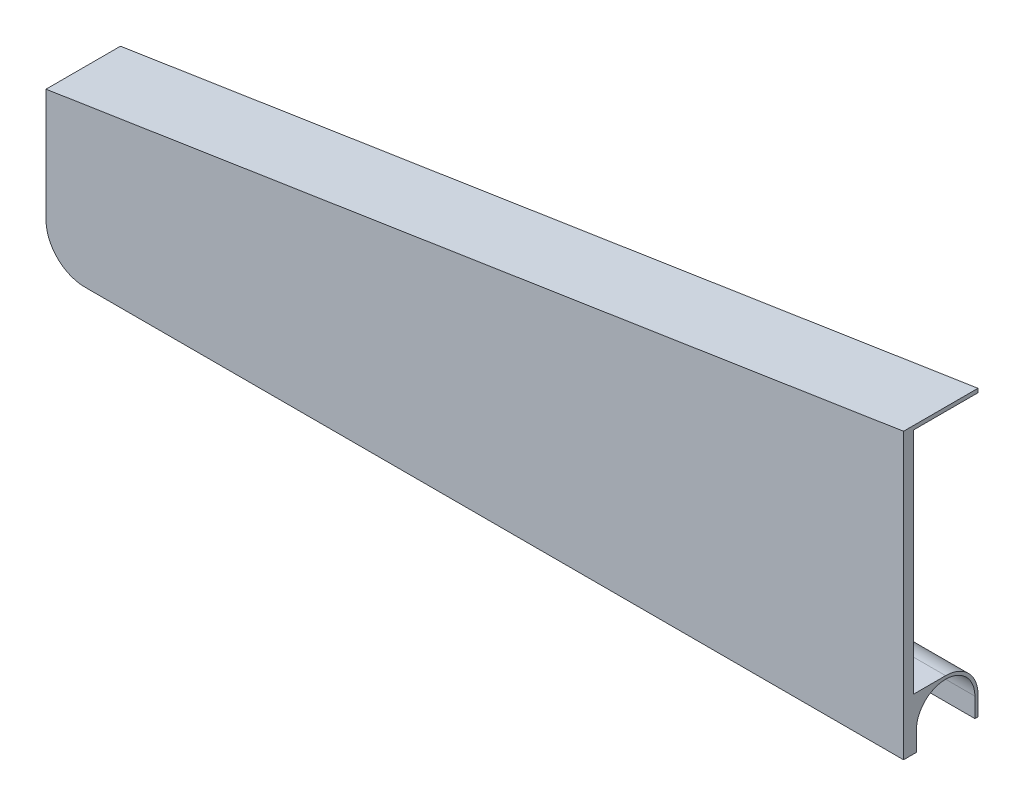
SolidWorks part; units mm, degrees
ref_plane "Front Plane" through (0, 0, 0) normal (0, 0, 1) x (1, 0, 0)
ref_plane "Top Plane" through (0, 0, 0) normal (0, 1, 0) x (1, 0, 0)
ref_plane "Right Plane" through (0, 0, 0) normal (1, 0, 0) x (0, 0, -1)
sketch "Sketch1" plane through (0, 0, 0) normal (0, 0, 1) x (1, 0, 0)
  line L14 (-508.0851, -168.7379) -> (-508.0851, -181.4379)
  line L15 (-482.6851, -206.8379) -> (50.7149, -206.8379)
  line L16 (50.7149, -21.4179) -> (50.7149, -206.8379)
  line L21 (-508.0851, -174.5299) -> (-506.3537, -154.7404) construction
  line L22 (50.7149, -21.4179) -> (-482.6851, -21.4179)
  line L23 (-508.0851, -46.8179) -> (-508.0851, -168.7379)
  line L25 (-280.355, -194.4538) -> (-508.0851, -174.5299) construction
  line L26 (-508.0851, -174.5299) -> (-506.3537, -154.7404) construction
  line L34 (50.264, -26.7703) -> (43.7726, -31.9989) construction
  line L35 (45.1252, -33.9002) -> (50.264, -26.7703) construction
  line L36 (43.7726, -31.9989) -> (45.1252, -33.9002) construction
  line L37 (50.264, -26.7703) -> (-103.8537, -138.7434) construction
  line L44 (-76.0701, -152.5352) -> (-303.6985, -173.5894) construction
  line L45 (-280.355, -194.4538) -> (-508.1812, -175.6608) construction
  arc A13 (-482.6851, -206.8379) -> (-508.0851, -181.4379) centre (-482.6851, -181.4379) cw
  arc A18 (-508.0851, -46.8179) -> (-482.6851, -21.4179) centre (-482.6851, -46.8179) cw
  spline S1 degree 3 poles (-77.3503, -153.028) (-75.7424, -152.4397) (-77.4131, -152.8082) (-78.8159, -153.009) (-82.1955, -153.6301) (-86.3746, -154.3457) (-91.8576, -155.2741) (-98.3546, -156.3306) (-105.8728, -157.5071) (-114.2967, -158.7552) (-123.5384, -160.0448) (-133.4905, -161.3332) (-144.0415, -162.5906) (-155.0756, -163.7834) (-166.472, -164.8921) (-178.1069, -165.8977) (-189.8537, -166.8034) (-201.5813, -167.5892) (-213.0987, -168.327) (-224.299, -168.8253) (-235.081, -169.0417) (-245.4007, -169.0644) (-255.1651, -168.9439) (-264.2735, -168.7565) (-272.6372, -168.5761) (-280.1622, -168.4631) (-286.7666, -168.4772) (-292.3689, -168.6848) (-296.9112, -169.1015) (-300.3402, -169.8135) (-302.7331, -170.728) (-304.0811, -172.4032) (-303.4934, -174.4785) (-301.6135, -176.2656) (-298.6237, -178.2272) (-294.381, -180.2447) (-288.9378, -182.3045) (-282.3217, -184.2798) (-274.6112, -186.0927) (-265.8938, -187.6285) (-256.2798, -188.797) (-245.8908, -189.5049) (-234.8632, -189.681) (-223.3425, -189.2828) (-211.5445, -188.2451) (-199.6188, -186.6868) (-187.6737, -184.833) (-175.7853, -182.6581) (-164.0807, -180.2199) (-152.6882, -177.5689) (-141.7311, -174.7614) (-131.3245, -171.8616) (-121.5743, -168.9396) (-112.5839, -166.062) (-104.4383, -163.3091) (-97.2161, -160.7402) (-91.0087, -158.4393) (-85.7953, -156.4423) (-81.8439, -154.8708) (-78.6405, -153.6118) (-77.3503, -153.028) (-75.7424, -152.4397) (-77.4131, -152.8082) knots -0.012273 -0.005484 -0.001375 0 0.001366 0.005489 0.012269 0.02165 0.033497 0.04769 0.06403 0.082338 0.102396 0.123959 0.146791 0.170641 0.19524 0.220332 0.245646 0.27091 0.295825 0.31977 0.342911 0.365083 0.386049 0.405629 0.423597 0.43978 0.453966 0.466008 0.475784 0.483219 0.48846 0.492078 0.495706 0.500976 0.508553 0.518608 0.53108 0.545907 0.56292 0.581928 0.60273 0.625094 0.648778 0.673537 0.699099 0.724814 0.750772 0.776731 0.802428 0.827555 0.851851 0.875071 0.896936 0.917223 0.935694 0.952169 0.966419 0.978318 0.987727 0.994516 0.998625 1 1.001366 1.005489 1.012269 only from (-76.0701, -152.5352) to (-76.0701, -152.5352) construction
  spline S6 degree 3 poles (43.7726, -31.9989) (42.2447, -33.2296) (40.7155, -34.4587) (37.6488, -36.9065) (36.1121, -38.1263) (31.4913, -41.7719) (28.3962, -44.1844) (19.0706, -51.36) (12.7967, -56.0605) (0.133, -65.2917) (-6.2572, -69.8216) (-19.1386, -78.7336) (-25.6299, -83.1155) (-35.4128, -89.621) (-38.6829, -91.7761) (-43.5886, -95.0079) (-45.2245, -96.0841) (-48.5114, -98.2146) (-50.1629, -99.2681) (-55.1382, -102.3978) (-58.4829, -104.4436) (-65.2122, -108.4767) (-68.5969, -110.4637) (-75.3814, -114.4158) (-78.7813, -116.3795) (-83.8592, -119.3606) (-85.548, -120.3605) (-88.9072, -122.3901) (-90.578, -123.4191) (-93.882, -125.538) (-95.5163, -126.6262) (-97.9049, -128.3604) (-98.6923, -128.9566) (-100.2178, -130.1983) (-100.9587, -130.8423) (-102.0031, -131.8787) (-102.3404, -132.2355) (-102.9811, -132.985) (-103.2858, -133.3815) (-103.8282, -134.2115) (-104.0657, -134.645) (-104.3302, -135.3457) (-104.4023, -135.5859) (-104.5056, -136.0708) (-104.5373, -136.3169) (-104.5503, -136.8183) (-104.5308, -137.0675) (-104.4365, -137.5532) (-104.3615, -137.7939) (-104.1647, -138.253) (-104.0443, -138.4697) (-103.7612, -138.8787) (-103.5969, -139.0714) (-103.2433, -139.4202) (-103.0526, -139.5787) (-102.6488, -139.8696) (-102.4352, -140.0024) (-101.7808, -140.3594) (-101.3217, -140.5456) (-100.3752, -140.8545) (-99.8916, -140.9757) (-98.9196, -141.1683) (-98.4293, -141.2409) (-97.4428, -141.3525) (-96.946, -141.3908) (-95.9572, -141.44) (-95.4638, -141.4515) (-93.986, -141.4541) (-93.0042, -141.4132) (-91.0449, -141.2727) (-90.0677, -141.172) (-88.1168, -140.9234) (-87.1432, -140.7753) (-85.1992, -140.4383) (-84.2286, -140.2495) (-81.3379, -139.633) (-79.4325, -139.155) (-73.7694, -137.5568) (-70.0643, -136.274) (-64.5922, -134.0851) (-62.78, -133.3095) (-59.1955, -131.6794) (-57.4277, -130.827) (-52.1921, -128.1664) (-48.792, -126.2547) (-42.1539, -122.1838) (-38.9157, -120.0249) (-32.5898, -115.4773) (-29.5085, -113.0789) (-24.9368, -109.4043) (-23.4229, -108.1642) (-20.4159, -105.6524) (-18.9236, -104.3816) (-11.5312, -97.9738) (-5.8211, -92.661) (5.2515, -81.7172) (10.6134, -76.0857) (21.018, -64.5307) (26.0603, -58.6066) (33.3882, -49.5051) (35.7913, -46.4351) (39.3365, -41.7756) (40.5082, -40.2133) (42.8316, -37.0704) (43.981, -35.4877) (45.1252, -33.9002) knots 0 0 0 0 0.015625 0.015625 0.03125 0.03125 0.0625 0.0625 0.125 0.125 0.1875 0.1875 0.25 0.25 0.28125 0.28125 0.296875 0.296875 0.3125 0.3125 0.34375 0.34375 0.375 0.375 0.40625 0.40625 0.421875 0.421875 0.4375 0.4375 0.453125 0.453125 0.460938 0.460938 0.46875 0.46875 0.472656 0.472656 0.476563 0.476563 0.480469 0.480469 0.482422 0.482422 0.484375 0.484375 0.486328 0.486328 0.488281 0.488281 0.490234 0.490234 0.492188 0.492188 0.494141 0.494141 0.496094 0.496094 0.5 0.5 0.503906 0.503906 0.507813 0.507813 0.511719 0.511719 0.515625 0.515625 0.523438 0.523438 0.53125 0.53125 0.539063 0.539063 0.546875 0.546875 0.5625 0.5625 0.59375 0.59375 0.609375 0.609375 0.625 0.625 0.65625 0.65625 0.6875 0.6875 0.71875 0.71875 0.734375 0.734375 0.75 0.75 0.8125 0.8125 0.875 0.875 0.9375 0.9375 0.96875 0.96875 0.984375 0.984375 1 1 1 1 construction
  spline S7 degree 3 poles (-281.7013, -194.7167) (-280.0158, -194.4166) (-281.7251, -194.4894) (-283.1414, -194.4435) (-286.5775, -194.4683) (-290.8174, -194.4474) (-296.3783, -194.4096) (-302.96, -194.3218) (-310.5683, -194.1749) (-319.0809, -193.9413) (-328.4062, -193.6065) (-338.4308, -193.1472) (-349.0399, -192.5533) (-360.1135, -191.8119) (-371.5293, -190.9248) (-383.162, -189.8947) (-394.8877, -188.7469) (-406.5735, -187.4843) (-418.044, -186.2108) (-429.1608, -184.7567) (-439.8165, -183.0975) (-449.9834, -181.3278) (-459.5785, -179.5136) (-468.516, -177.7475) (-476.7213, -176.1174) (-484.1124, -174.6994) (-490.6189, -173.5664) (-496.1721, -172.7981) (-500.7178, -172.4197) (-504.2183, -172.5255) (-506.7336, -173.0106) (-508.3521, -174.4262) (-508.1337, -176.572) (-506.5927, -178.6584) (-503.9889, -181.1094) (-500.161, -183.833) (-495.1582, -186.8067) (-488.9856, -189.9009) (-481.7071, -193.0251) (-473.3887, -196.0514) (-464.1238, -198.8715) (-454.0155, -201.3728) (-443.186, -203.461) (-431.7712, -205.0695) (-419.9722, -206.0963) (-407.9571, -206.6325) (-395.8716, -206.8811) (-383.7862, -206.8037) (-371.836, -206.435) (-360.1562, -205.8025) (-348.878, -204.9404) (-338.126, -203.8917) (-328.0166, -202.7072) (-318.663, -201.4345) (-310.1631, -200.1379) (-302.6046, -198.8621) (-296.0919, -197.6741) (-290.6109, -196.6127) (-286.4467, -195.7513) (-283.0733, -195.0676) (-281.7013, -194.7167) (-280.0158, -194.4166) (-281.7251, -194.4894) knots -0.012273 -0.005484 -0.001375 0 0.001366 0.005489 0.012269 0.02165 0.033497 0.04769 0.06403 0.082338 0.102396 0.123959 0.146791 0.170641 0.19524 0.220332 0.245646 0.27091 0.295825 0.31977 0.342911 0.365083 0.386049 0.405629 0.423597 0.43978 0.453966 0.466008 0.475784 0.483219 0.48846 0.492078 0.495706 0.500976 0.508553 0.518608 0.53108 0.545907 0.56292 0.581928 0.60273 0.625094 0.648778 0.673537 0.699099 0.724814 0.750772 0.776731 0.802428 0.827555 0.851851 0.875071 0.896936 0.917223 0.935694 0.952169 0.966419 0.978318 0.987727 0.994516 0.998625 1 1.001366 1.005489 1.012269 only from (-280.355, -194.4538) to (-280.355, -194.4538) construction
  point P27 (-280.355, -194.4538)
  dimension "D1" = 508.0851
  dimension "D2" = 25.4
  dimension "D4" = 12.7
  dimension "D7" = 25.4
  dimension "D8" = 21.4179
  dimension "D5" = 185.42
  dimension "D6" = 558.8
extrude "Boss-Extrude1" add sketch "Sketch1" along normal blind 6.35
ref_plane "Plane1" through (-508.0851, -181.4379, 6.35) normal (1, 0, 0) x (0, 0, -1)
sketch "Sketch2" plane through (50.7149, 0, 0) normal (1, 0, 0) x (0, 0, -1)
  line L0 (21.082, -173.0559) -> (0, -173.0559)
  line L1 (0, -206.8379) -> (2.032, -206.8379)
  line L2 (0, -206.8379) -> (0, -194.1379)
  line L4 (2.032, -206.8379) -> (2.032, -194.1379)
  line L5 (40.132, -206.8379) -> (42.164, -206.8379)
  line L6 (40.132, -206.8379) -> (40.132, -194.1379)
  line L8 (42.164, -206.8379) -> (42.164, -194.1379)
  line L9 (0, -174.5299) -> (0, -154.7404) construction
  line L10 (0, -173.0559) -> (0, -194.1379)
  arc A0 (0, -194.1379) -> (42.164, -194.1379) centre (21.082, -194.1379) cw
  arc A1 (2.032, -194.1379) -> (40.132, -194.1379) centre (21.082, -194.1379) cw
  line M11 (0, -206.8379) -> (0, -21.4179)
  dimension "D1" = 19.05
  dimension "D2" = 21.082
  dimension "D3" = 12.7
extrude "Boss-Extrude2" add sketch "Sketch2" against normal through all contours A0 L0 M11
sketch "Sketch3" plane through (0, 0, 0) normal (0, 0, 1) x (1, 0, 0)
  line L2 (-508.0851, -206.8379) -> (-482.6851, -206.8379)
  line L3 (-508.0851, -181.4379) -> (-508.0851, -206.8379)
  line L4 (-508.0851, -206.8379) -> (-482.6851, -206.8379)
  line L5 (-508.0851, -181.4379) -> (-508.0851, -206.8379)
  arc A1 (-508.0851, -181.4379) -> (-482.6851, -206.8379) centre (-482.6851, -181.4379) ccw
  arc A2 (-508.0851, -181.4379) -> (-482.6851, -206.8379) centre (-482.6851, -181.4379) ccw
  dimension "D1" = 0
extrude "Cut-Extrude1" cut sketch "Sketch3" against normal blind 93.726
sketch "Sketch4" plane through (0, 0, 0) normal (0, 0, -1) x (-1, 0, 0)
  line L0 (-50.7149, -21.4179) -> (508.0851, -107.7779)
  line L1 (508.0851, -46.8179) -> (508.0851, -168.7379) construction
  line L2 (-50.7149, -21.4179) -> (482.6851, -21.4179) construction
  line L3 (-50.7149, -21.4179) -> (482.6851, -21.4179)
  line L4 (508.0851, -46.8179) -> (508.0851, -168.7379)
  arc A0 (508.0851, -46.8179) -> (482.6851, -21.4179) centre (482.6851, -46.8179) ccw construction
  arc A1 (508.0851, -46.8179) -> (482.6851, -21.4179) centre (482.6851, -46.8179) ccw
  line M3 (508.0851, -173.0559) -> (508.0851, -46.8179)
  arc M4 (508.0851, -46.8179) -> (482.6851, -21.4179) centre (482.6851, -46.8179) ccw
  line M5 (482.6851, -21.4179) -> (-50.7149, -21.4179)
extrude "Cut-Extrude2" cut sketch "Sketch4" against normal blind 93.726 contours L0 M5 M3 M4
sketch "Sketch5" plane through (0, 0, 0) normal (0, 0, -1) x (-1, 0, 0)
  line L0 (-50.7149, -21.4179) -> (508.0851, -107.7779)
  line L1 (508.0851, -46.8179) -> (508.0851, -168.7379) construction
  line L2 (508.0851, -107.7779) -> (508.0851, -110.3179)
  line L3 (-50.7149, -21.4179) -> (-50.7149, -23.9579)
  line L4 (-50.7149, -21.4179) -> (-50.7149, -206.8379) construction
  line L5 (-50.7149, -23.9579) -> (508.0851, -110.3179)
  dimension "D1" = 2.54
  dimension "D2" = 2.54
extrude "Boss-Extrude3" add sketch "Sketch5" along normal through all
